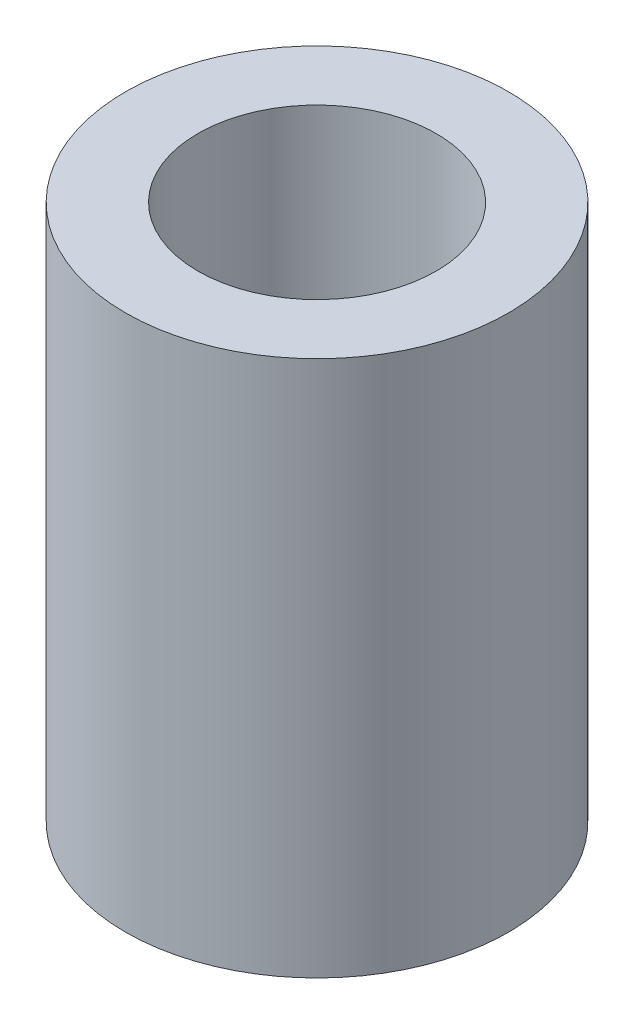
SolidWorks part; units mm, degrees
ref_plane "前视基准面" through (0, 0, 0) normal (0, 0, 1) x (1, 0, 0)
ref_plane "上视基准面" through (0, 0, 0) normal (0, 1, 0) x (1, 0, 0)
ref_plane "右视基准面" through (0, 0, 0) normal (1, 0, 0) x (0, 0, -1)
sketch "草图1" plane through (0, 0, 0) normal (0, 1, 0) x (1, 0, 0)
  circle A0 centre (0, 0) radius 2.25
  dimension "D1" = 4.5
extrude "拉伸1" add sketch "草图1" along normal blind 6.3
sketch "草图2" plane through (0, 6.3, 0) normal (0, 1, 0) x (1, 0, 0)
  circle A0 centre (0, 0) radius 1.4
  dimension "D1" = 2.8
extrude "拉伸2" cut sketch "草图2" against normal blind 3.3
